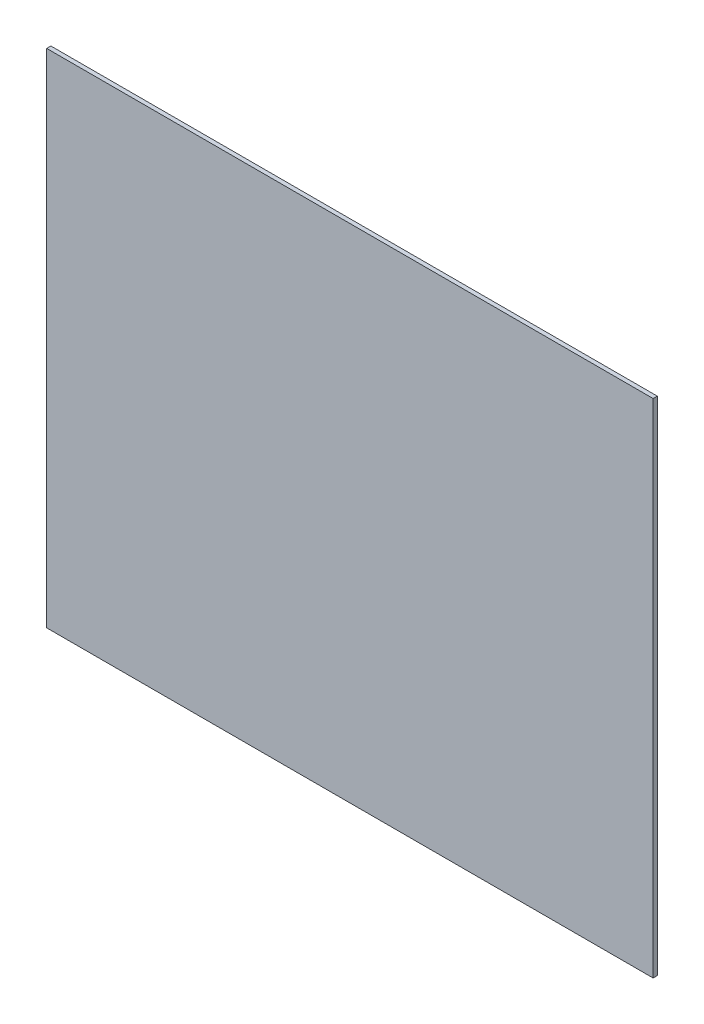
SolidWorks part; units mm, degrees
material "BUTYL"
ref_plane "Front Plane" through (0, 0, 0) normal (0, 0, 1) x (1, 0, 0)
ref_plane "Top Plane" through (0, 0, 0) normal (0, 1, 0) x (1, 0, 0)
ref_plane "Right Plane" through (0, 0, 0) normal (1, 0, 0) x (0, 0, -1)
sketch "Sketch1" plane through (0, 0, 0) normal (0, 0, 1) x (1, 0, 0)
  line L4 (0, 0) -> (0, 240)
  line L5 (0, 240) -> (-290, 240)
  line L6 (-290, 240) -> (-290, 0)
  line L7 (-290, 0) -> (0, 0)
  line L8 (0, 0) -> (0, 240)
  line L9 (0, 240) -> (-290, 240)
  line L10 (-290, 240) -> (-290, 0)
  line L11 (-290, 0) -> (0, 0)
  dimension "D1" = 0
extrude "Boss-Extrude1" add sketch "Sketch1" along normal blind 2
